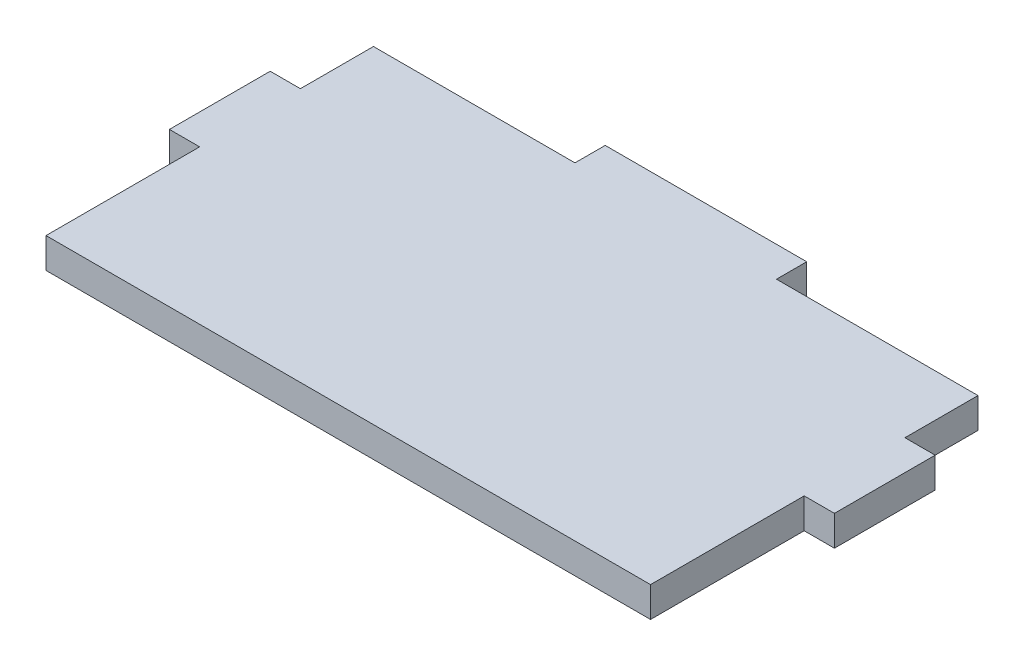
SolidWorks part; units mm, degrees
ref_plane "Front Plane" through (0, 0, 0) normal (0, 0, 1) x (1, 0, 0)
ref_plane "Top Plane" through (0, 0, 0) normal (0, 1, 0) x (1, 0, 0)
ref_plane "Right Plane" through (0, 0, 0) normal (1, 0, 0) x (0, 0, -1)
sketch "Sketch2" plane through (0, 0, 0) normal (0, 1, 0) x (1, 0, 0)
  line L1 (-30, 17.75) -> (30, 17.75)
  line L2 (-30, 17.75) -> (-30, -17.75)
  line L3 (-30, -17.75) -> (30, -17.75)
  line L4 (30, 17.75) -> (30, -17.75)
  line L5 (-30, 17.75) -> (30, -17.75) construction
  line L6 (-30, -17.75) -> (30, 17.75) construction
  point P0 (0, 0)
  dimension "D1" = 60
  dimension "D2" = 35.5
extrude "Boss-Extrude1" add sketch "Sketch2" along normal blind 3
sketch "Sketch3" plane through (0, 0, 0) normal (0, 1, 0) x (1, 0, 0)
  line L0 (-30, 7.5) -> (-33, 7.5)
  line L1 (-30, 17.75) -> (-30, -17.75) construction
  line L2 (-33, 7.5) -> (-33, -2.5)
  line L3 (-33, -2.5) -> (-30, -2.5)
  line L4 (-30, -2.5) -> (-30, 7.5)
  line L5 (30, 7.5) -> (33, 7.5)
  line L6 (30, -17.75) -> (30, 17.75) construction
  line L7 (33, 7.5) -> (33, -2.5)
  line L8 (33, -2.5) -> (30, -2.5)
  line L9 (30, -2.5) -> (30, 7.5)
  line L10 (30, 17.75) -> (-30, 17.75) construction
  point P10 (33, 2.5)
  point P13 (-33, 2.5)
  dimension "D1" = 3
  dimension "D2" = 10
  dimension "D3" = 15.25
  dimension "D4" = 15.25
extrude "Boss-Extrude2" add sketch "Sketch3" along normal blind 3
sketch "Sketch4" plane through (0, 3, 0) normal (0, 1, 0) x (1, 0, 0)
  line L0 (-10, 17.75) -> (-10, 14.75)
  line L1 (30, 17.75) -> (-30, 17.75) construction
  line L2 (-10, 14.75) -> (10, 14.75)
  line L3 (10, 14.75) -> (10, 17.75)
  line L4 (0, 14.75) -> (0, 17.75) construction
  line L5 (-10, 17.75) -> (10, 17.75)
  line L6 (-10, 14.75) -> (-30, 14.75)
  line L7 (-30, 17.75) -> (-30, 7.5) construction
  line L8 (-30, 14.75) -> (-30, 17.75)
  line L9 (-30, 17.75) -> (-10, 17.75)
  line L10 (10, 14.75) -> (30, 14.75)
  line L11 (30, 7.5) -> (30, 17.75) construction
  line L12 (30, 14.75) -> (30, 17.75)
  line L13 (30, 17.75) -> (10, 17.75)
  line M8 (30, 7.5) -> (30, 17.75)
  line M9 (30, 17.75) -> (-30, 17.75)
  line M10 (-30, 17.75) -> (-30, 7.5)
  dimension "D1" = 3
  dimension "D2" = 20
extrude "Cut-Extrude2" cut sketch "Sketch4" against normal blind 3 contours L6 L0 M9 M10 | L3 L10 M8 M9
